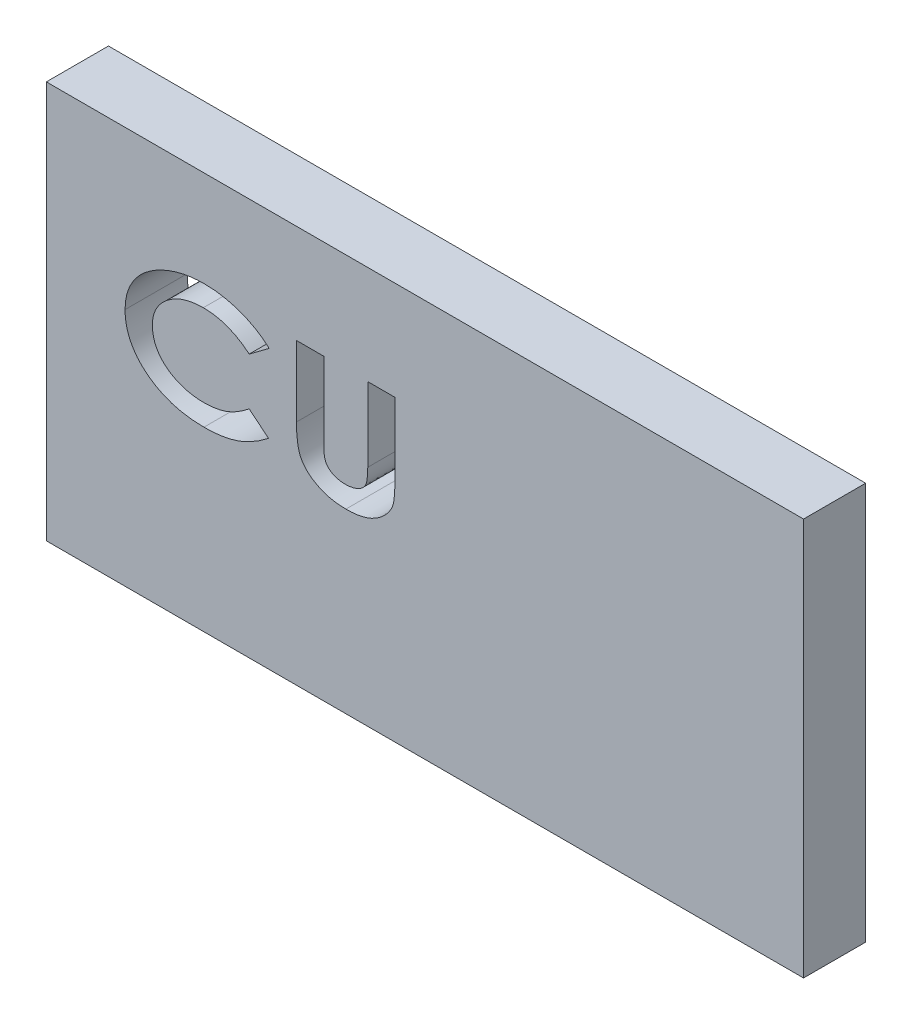
SolidWorks part; units mm, degrees
material "PBT General Purpose"
ref_plane "Front Plane" through (0, 0, 0) normal (0, 0, 1) x (1, 0, 0)
ref_plane "Top Plane" through (0, 0, 0) normal (0, 1, 0) x (1, 0, 0)
ref_plane "Right Plane" through (0, 0, 0) normal (1, 0, 0) x (0, 0, -1)
sketch "Sketch1" plane through (0, 0, 0) normal (0, 0, 1) x (1, 0, 0)
  line L0 (0, 0) -> (0, 32)
  line L1 (0, 32) -> (60.96, 32)
  line L2 (60.96, 32) -> (60.96, 0)
  line L3 (60.96, 0) -> (0, 0)
extrude "Boss-Extrude1" add sketch "Sketch1" along normal blind 5 contours L0 L1 L2 L3
sketch "Sketch2" plane through (0, 0, 5) normal (0, 0, 1) x (1, 0, 0)
  text T0 "CU" font "Century Gothic" height in points 36
extrude "Emboss ID" cut sketch "Sketch2" against normal through all
